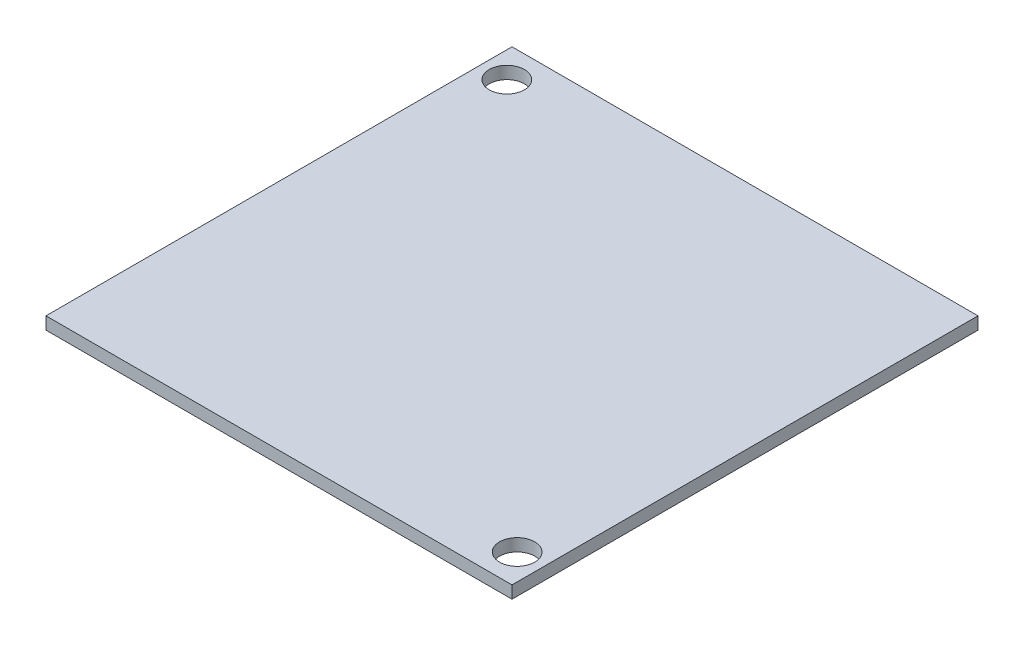
SolidWorks part; units mm, degrees
ref_plane "Front Plane" through (0, 0, 0) normal (0, 0, 1) x (1, 0, 0)
ref_plane "Top Plane" through (0, 0, 0) normal (0, 1, 0) x (1, 0, 0)
ref_plane "Right Plane" through (0, 0, 0) normal (1, 0, 0) x (0, 0, -1)
sketch "Sketch1" plane through (0, 0, 0) normal (0, 1, 0) x (1, 0, 0)
  line L1 (-24.7775, 1.3586) -> (20.2225, 1.3586)
  line L2 (-24.7775, 1.3586) -> (-24.7775, -43.6414)
  line L3 (-24.7775, -43.6414) -> (20.2225, -43.6414)
  line L4 (20.2225, 1.3586) -> (20.2225, -43.6414)
  dimension "D1" = 45
  dimension "D2" = 45
extrude "Boss-Extrude1" add sketch "Sketch1" along normal blind 1.2
hole_wizard "M3 Clearance Hole1" positions "3DSketch1" profile "Sketch2" hole size "M3" standard "ANSI Metric" end condition through all
sketch3d "3DSketch1"
  line L0 (-24.7775, 1.2, 43.6414) -> (20.2225, 1.2, 43.6414) construction
  line L1 (20.2225, 1.2, 43.6414) -> (20.2225, 1.2, -1.3586) construction
  line L2 (-24.7775, 1.2, -1.3586) -> (-24.7775, 1.2, 43.6414) construction
  line L3 (20.2225, 1.2, -1.3586) -> (-24.7775, 1.2, -1.3586) construction
  point P0 (-22.2775, 1.2, 1.6414)
  point P2 (17.7225, 1.2, 40.6414)
  dimension "D1" = 3
  dimension "D2" = 2.5
  dimension "D3" = 2.5
  dimension "D4" = 3
sketch "Sketch2" plane through (-22.2775, 1.2, 1.6414) normal (1, 0, 0) x (0, 0, 1)
  line L0 (0, 0) -> (0, 1.2)
  line L1 (0, 1.2) -> (1.7, 1.2)
  line L2 (1.7, 1.2) -> (1.7, 0)
  line L5 (1.7, 0) -> (0, 0)
  line L11 (0, -6.35) -> (0, 107.95) construction
  dimension "Thru Hole Dia." = 3.4
  dimension "Thru Hole Depth" = 1.2
